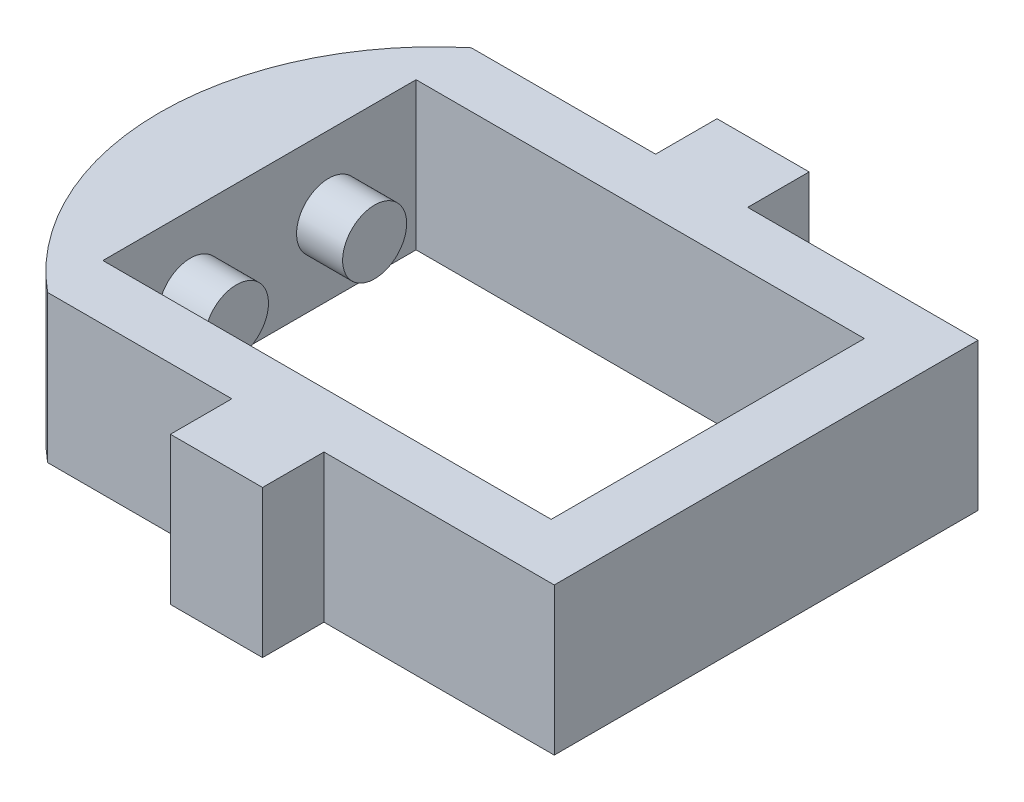
SolidWorks part; units mm, degrees
ref_plane "Front Plane" through (0, 0, 0) normal (0, 0, 1) x (1, 0, 0)
ref_plane "Top Plane" through (0, 0, 0) normal (0, 1, 0) x (1, 0, 0)
ref_plane "Right Plane" through (0, 0, 0) normal (1, 0, 0) x (0, 0, -1)
sketch "Sketch1" plane through (0, 0, 0) normal (0, 1, 0) x (1, 0, 0)
  line L0 (-18, 13.8) -> (-6, 13.8)
  line L1 (-6, 13.8) -> (-6, 17.8)
  line L2 (-6, 17.8) -> (0, 17.8)
  line L3 (0, 17.8) -> (0, 13.8)
  line L8 (-18, 10.2) -> (0, 10.2)
  line L9 (-18, 10.2) -> (-18, -10.2)
  line L10 (0, -10.2) -> (-18, -10.2)
  line L19 (0, 13.8) -> (0, 10.2)
  line L20 (0, -10.2) -> (0, -13.8)
  line L21 (0, 10.2) -> (11.2, 10.2)
  line L22 (11.2, 10.2) -> (11.2, -10.2)
  line L23 (11.2, -10.2) -> (0, -10.2)
  line L24 (0, -13.8) -> (15, -13.8)
  line L25 (15, -13.8) -> (15, 13.8)
  line L26 (15, 13.8) -> (0, 13.8)
  line L29 (-18, -13.8) -> (-6, -13.8)
  line L30 (-6, -13.8) -> (-6, -17.8)
  line L31 (-6, -17.8) -> (0, -17.8)
  line L32 (0, -17.8) -> (0, -13.8)
  arc A3 (-18, 13.8) -> (-18, -13.8) centre (-6.6008, 0) ccw
  point P5 (-24.5, 0)
  point P24 (-18, 0)
  point P30 (0, 15.8)
  dimension "D1" = 3.6
  dimension "D2" = 4
  dimension "D3" = 6
  dimension "D4" = 3.8
  dimension "D5" = 15
  dimension "D6" = 6.5
  dimension "D7" = 27.6
  dimension "D9" = 18
extrude "Boss-Extrude1" add sketch "Sketch1" along normal blind 9.6
sketch "Sketch3" plane through (-18, 0, 0) normal (1, 0, 0) x (0, 0, -1)
  line L0 (-10.2, 4.8) -> (-4.5, 4.8) construction
  line L1 (-10.2, 9.6) -> (-10.2, 0) construction
  line L2 (-4.5, 4.8) -> (4.5, 4.8) construction
  line L3 (4.5, 4.8) -> (10.2, 4.8) construction
  line L4 (10.2, 9.6) -> (10.2, 0) construction
  circle A0 centre (-4.5, 4.8) radius 2.085
  circle A1 centre (4.5, 4.8) radius 2.085
  dimension "D1" = 4.17
  dimension "D2" = 9
extrude "Boss-Extrude3" add sketch "Sketch3" along normal blind 3
